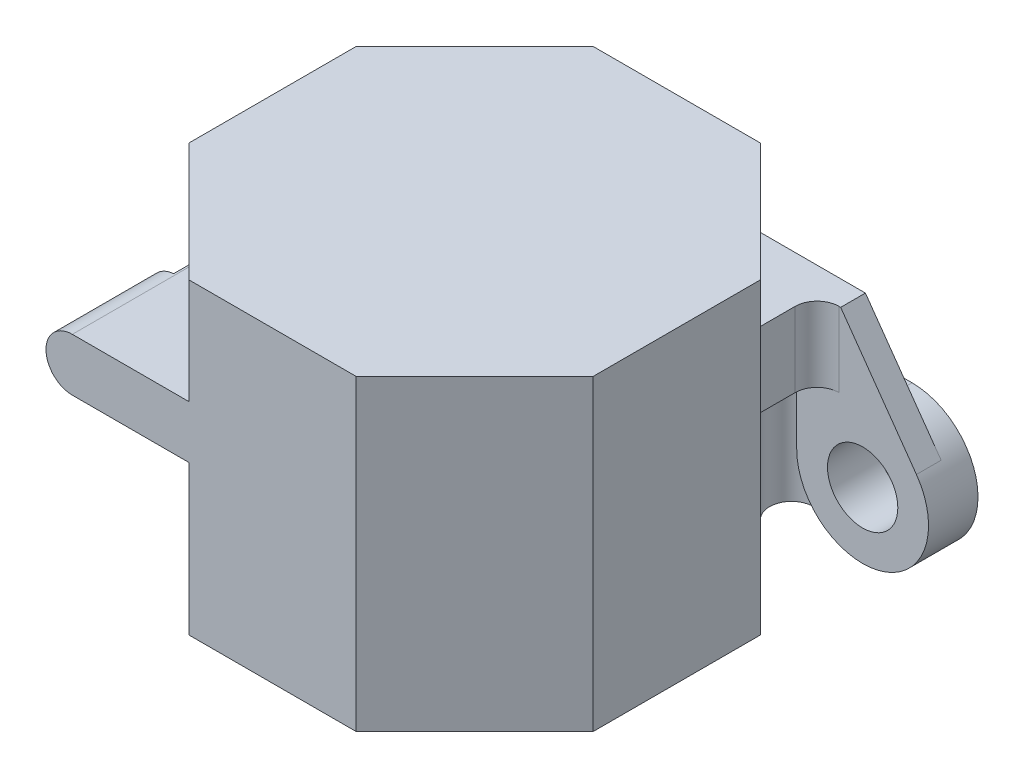
SolidWorks part; units mm, degrees
material "ABS"
ref_plane "Front Plane" through (0, 0, 0) normal (0, 0, 1) x (1, 0, 0)
ref_plane "Top Plane" through (0, 0, 0) normal (0, 1, 0) x (1, 0, 0)
ref_plane "Right Plane" through (0, 0, 0) normal (1, 0, 0) x (0, 0, -1)
sketch "Sketch1" plane through (0, 0, 0) normal (0, 1, 0) x (1, 0, 0)
  line L1 (9.6793, -23.368) -> (23.368, -9.6793)
  line L2 (23.368, -9.6793) -> (23.368, 9.6793)
  line L3 (23.368, 9.6793) -> (9.6793, 23.368)
  line L4 (9.6793, 23.368) -> (-9.6793, 23.368)
  line L5 (-9.6793, 23.368) -> (-23.368, 9.6793)
  line L6 (-23.368, 9.6793) -> (-23.368, -9.6793)
  line L7 (-23.368, -9.6793) -> (-9.6793, -23.368)
  line L8 (-9.6793, -23.368) -> (9.6793, -23.368)
  circle A0 centre (0, 0) radius 23.368 construction
  dimension "D1" = 46.736
extrude "Boss-Extrude1" add sketch "Sketch1" along normal blind 35.56
shell "Shell1" thickness 2.032
sketch "Sketch2" plane through (0, 0, 0) normal (0, -1, 0) x (1, 0, 0)
  line L0 (23.368, 9.6793) -> (23.368, -9.6793) construction
  line L1 (23.368, 9.6793) -> (9.6793, 23.368)
  line L2 (9.6793, 23.368) -> (-9.6793, 23.368)
  line L3 (-9.6793, 23.368) -> (-23.368, 9.6793)
  line L4 (-23.368, 9.6793) -> (-23.368, -9.6793)
  line L5 (-23.368, -9.6793) -> (-9.6793, -23.368)
  line L6 (-9.6793, -23.368) -> (9.6793, -23.368)
  line L7 (9.6793, -23.368) -> (23.368, -9.6793)
  line L8 (23.368, -9.6793) -> (23.368, 9.6793)
  circle A0 centre (0, 0) radius 23.368 construction
  circle A1 centre (0, 0) radius 15.24
  dimension "D1" = 30.48
extrude "Boss-Extrude2" add sketch "Sketch2" against normal blind 3.175
sketch "Sketch3" plane through (0, 0, -23.368) normal (0, 0, -1) x (-1, 0, 0)
  line L0 (-9.6793, 35.56) -> (-9.6793, 0) construction
  line L1 (-9.6793, 5.08) -> (-27.2053, 5.08)
  line L2 (-9.6793, 5.08) -> (-9.6793, 20.32)
  line L3 (-9.6793, 20.32) -> (-27.2053, 20.32)
  line L5 (-34.8253, 12.7) -> (-9.6793, 12.7) construction
  line L6 (-23.368, 0) -> (-9.6793, 0) construction
  arc A0 (-27.2053, 20.32) -> (-27.2053, 5.08) centre (-27.2053, 12.7) ccw
  circle A1 centre (-27.2053, 12.7) radius 4.064
  dimension "D2" = 8.128
  dimension "D1" = 15.24
  dimension "D3" = 25.146
  dimension "D4" = 20.32
extrude "Boss-Extrude3" add sketch "Sketch3" against normal blind 2.8575
fillet "Fillet2" radius 2.54 1 edges at (12.5368, 12.7, -20.5105)
sketch "Sketch4" plane through (0, 0, -20.5105) normal (0, 0, 1) x (1, 0, 0)
  line L5 (12.9813, 19.304) -> (12.9813, 29.464)
  line L7 (12.9813, 29.464) -> (24.6653, 29.464)
  line L8 (24.6653, 29.464) -> (33.4226, 17.1056)
  line L9 (34.8253, 12.7) -> (24.6653, 12.7) construction
  line L10 (24.6653, 12.7) -> (24.6653, 29.464) construction
  line L11 (9.6793, 35.56) -> (9.6793, 20.32) construction
  line L12 (19.5853, 12.7) -> (19.5853, 19.304)
  line L13 (19.5853, 19.304) -> (12.9813, 19.304)
  line L14 (9.6793, 20.32) -> (27.2053, 20.32) construction
  circle A0 centre (27.2053, 12.7) radius 4.064
  circle A1 centre (27.2053, 12.7) radius 4.064 construction
  arc A3 (19.5853, 12.7) -> (33.4226, 17.1056) centre (27.2053, 12.7) ccw
  dimension "D1" = 10.16
  dimension "D2" = 10.16
  dimension "D3" = 3.302
  dimension "D4" = 1.016
extrude "Boss-Extrude10" add sketch "Sketch4" along normal blind 2.8575
sketch "Sketch5" plane through (0, 29.464, 0) normal (0, 1, 0) x (1, 0, 0)
  line L0 (12.5368, 20.5105) -> (21.9348, 20.5105)
  line L2 (21.9348, 20.5105) -> (21.9348, 11.1125)
  line L4 (21.9348, 11.1125) -> (12.5368, 20.5105)
  line L10 (24.6653, 20.5105) -> (12.9813, 20.5105) construction
  line L11 (23.368, 9.6793) -> (9.6793, 23.368) construction
  dimension "D1" = 9.398
extrude "Boss-Extrude11" add sketch "Sketch5" against normal blind 8.636
fillet "Fillet3" radius 2.54 1 edges at (21.9348, 25.146, -17.653)
sketch "Sketch6" plane through (0, 0, 23.368) normal (0, 0, 1) x (1, 0, 0)
  line L0 (-9.6793, 35.56) -> (-9.6793, 0) construction
  line L1 (-9.6793, 17.272) -> (-23.1413, 17.272)
  line L2 (-9.6793, 17.272) -> (-9.6793, 23.368)
  line L3 (-9.6793, 23.368) -> (-23.1413, 23.368)
  line L8 (-26.1893, 20.32) -> (-9.6793, 20.32) construction
  line L11 (9.6793, 20.32) -> (27.2053, 20.32) construction
  arc A0 (-23.1413, 23.368) -> (-23.1413, 17.272) centre (-23.1413, 20.32) ccw
  dimension "D1" = 6.096
  dimension "D2" = 16.51
extrude "Boss-Extrude12" add sketch "Sketch6" against normal through all
sketch "Sketch8" plane through (0, 35.56, 0) normal (0, 1, 0) x (1, 0, 0)
  line L1 (-23.368, 11.43) -> (-28.448, 11.43)
  line L2 (-23.368, 11.43) -> (-23.368, -11.43)
  line L3 (-23.368, -11.43) -> (-28.448, -11.43)
  line L4 (-28.448, 11.43) -> (-28.448, -11.43)
  line L5 (-23.368, 9.6793) -> (-23.368, -9.6793) construction
  point P6 (-23.368, 0)
  dimension "D1" = 5.08
  dimension "D2" = 22.86
extrude "Cut-Extrude1" cut sketch "Sketch8" against normal through all
